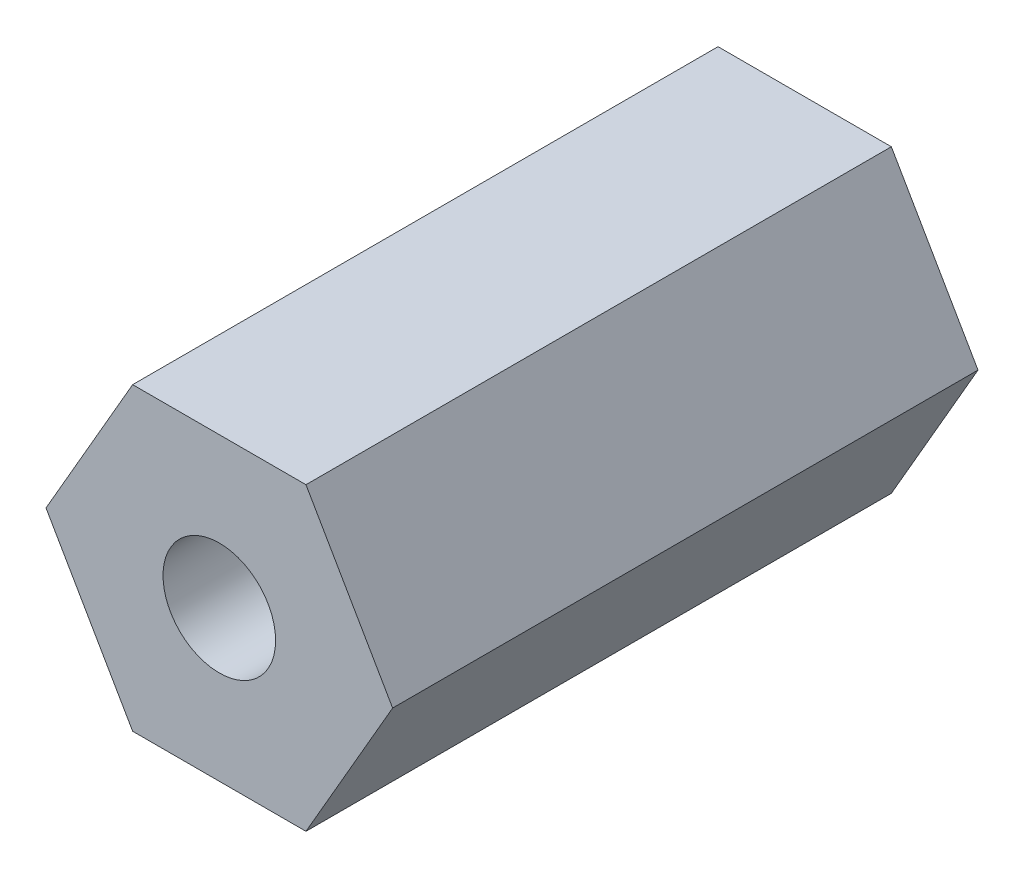
SolidWorks part; units mm, degrees
ref_plane "前视基准面" through (0, 0, 0) normal (0, 0, 1) x (1, 0, 0)
ref_plane "上视基准面" through (0, 0, 0) normal (0, 1, 0) x (1, 0, 0)
ref_plane "右视基准面" through (0, 0, 0) normal (1, 0, 0) x (0, 0, -1)
sketch "草图1" plane through (0, 0, 0) normal (0, 0, 1) x (1, 0, 0)
  line L1 (2.3094, 4) -> (-2.3094, 4)
  line L2 (-2.3094, 4) -> (-4.6188, 0)
  line L3 (-4.6188, 0) -> (-2.3094, -4)
  line L4 (-2.3094, -4) -> (2.3094, -4)
  line L5 (2.3094, -4) -> (4.6188, 0)
  line L6 (4.6188, 0) -> (2.3094, 4)
  circle A0 centre (0, 0) radius 1.5
  circle A1 centre (0, 0) radius 4 construction
  dimension "D1" = 3
  dimension "D2" = 8
extrude "凸台-拉伸1" add sketch "草图1" along normal blind 15.6
